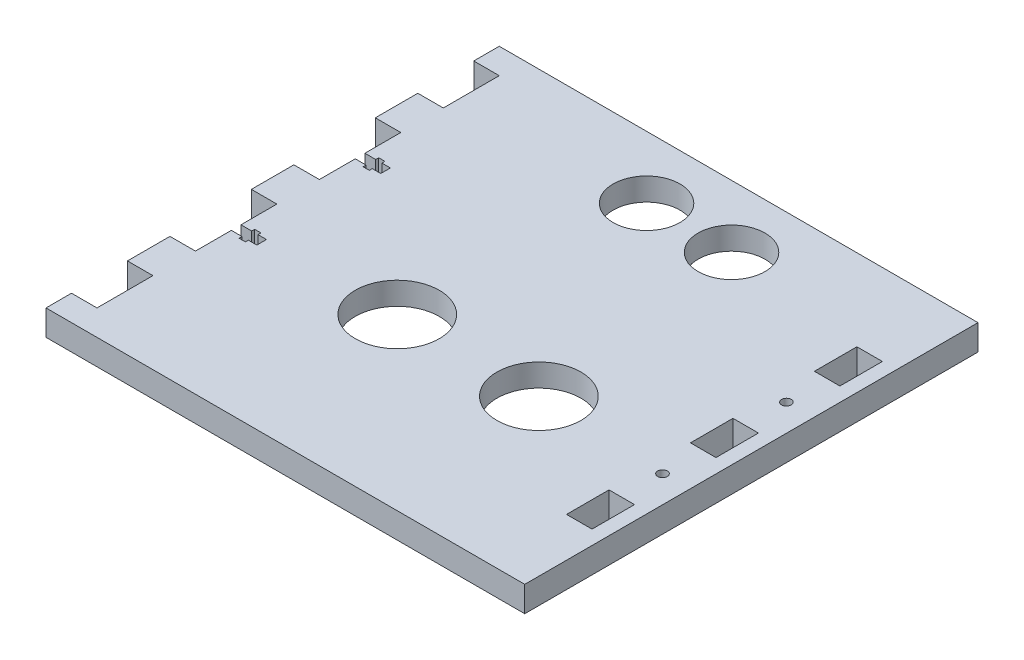
SolidWorks part; units mm, degrees
ref_plane "Front Plane" through (0, 0, 0) normal (0, 0, 1) x (1, 0, 0)
ref_plane "Top Plane" through (0, 0, 0) normal (0, 1, 0) x (1, 0, 0)
ref_plane "Right Plane" through (0, 0, 0) normal (1, 0, 0) x (0, 0, -1)
sketch "Sketch1" plane through (0, 0, 0) normal (0, 1, 0) x (1, 0, 0)
  line L1 (80, -80) -> (-80, -80)
  line L2 (80, -80) -> (80, 80)
  line L3 (80, 80) -> (-80, 80)
  line L4 (-80, -80) -> (-80, 80)
  line L5 (80, -80) -> (-80, 80) construction
  line L6 (80, 80) -> (-80, -80) construction
  point P0 (0, 0)
  dimension "D1" = 160
extrude "Boss-Extrude1" add sketch "Sketch1" along normal blind 9
sketch "Sketch2" plane through (0, 9, 0) normal (0, 1, 0) x (1, 0, 0)
  line L0 (-80, 80) -> (-80, -80) construction
  line L1 (-80, -7.5) -> (-89, -7.5)
  line L2 (-80, -7.5) -> (-80, 7.5)
  line L3 (-80, 7.5) -> (-89, 7.5)
  line L4 (-89, -7.5) -> (-89, 7.5)
  line L5 (-80, 0) -> (0, 0) construction
  line L6 (-80, 80) -> (-80, 51.25) construction
  line L7 (-80, 51.25) -> (-89, 51.25)
  line L8 (-80, 51.25) -> (-80, 36.25)
  line L9 (-80, 36.25) -> (-89, 36.25)
  line L10 (-89, 51.25) -> (-89, 36.25)
  line L11 (-80, -36.25) -> (-89, -36.25)
  line L12 (-80, -36.25) -> (-80, -51.25)
  line L13 (-80, -51.25) -> (-89, -51.25)
  line L14 (-89, -36.25) -> (-89, -51.25)
  line L15 (-80, 36.25) -> (-80, 7.5) construction
  line L16 (-80, -7.5) -> (-80, -36.25) construction
  line L17 (-80, -51.25) -> (-80, -80) construction
  line L19 (-80, 80) -> (-89, 80)
  line L20 (-80, 80) -> (-80, 71)
  line L21 (-80, 71) -> (-89, 71)
  line L22 (-89, 80) -> (-89, 71)
  line L23 (-80, -80) -> (-89, -80)
  line L24 (-80, -80) -> (-80, -71)
  line L25 (-80, -71) -> (-89, -71)
  line L26 (-89, -80) -> (-89, -71)
  dimension "D1" = 9
  dimension "D2" = 15
  dimension "D3" = 9
extrude "Boss-Extrude2" add sketch "Sketch2" against normal up to surface (9 mm away) up to face at (0, 0, 0)
sketch "Sketch3" plane through (0, 9, 0) normal (0, 1, 0) x (1, 0, 0)
  line L1 (75, 51.25) -> (66, 51.25)
  line L2 (75, 51.25) -> (75, 36.25)
  line L3 (75, 36.25) -> (66, 36.25)
  line L4 (66, 51.25) -> (66, 36.25)
  line L5 (-80, 51.25) -> (-89, 51.25) construction
  line L6 (75, 7.5) -> (66, 7.5)
  line L7 (75, 7.5) -> (75, -7.5)
  line L8 (75, -7.5) -> (66, -7.5)
  line L9 (66, 7.5) -> (66, -7.5)
  line L10 (75, -36.25) -> (66, -36.25)
  line L11 (75, -36.25) -> (75, -51.25)
  line L12 (75, -51.25) -> (66, -51.25)
  line L13 (66, -36.25) -> (66, -51.25)
  line L14 (-80, 7.5) -> (-89, 7.5) construction
  line L15 (-89, -7.5) -> (-80, -7.5) construction
  line L16 (-89, -51.25) -> (-80, -51.25) construction
  line L17 (80, -80) -> (80, 80) construction
  line L18 (70.5, 36.25) -> (70.5, 7.5) construction
  line L19 (70.5, 7.5) -> (70.5, -7.5) construction
  line L20 (70.5, -7.5) -> (70.5, -36.25) construction
  line L21 (70.5, -36.25) -> (70.5, -51.25) construction
  line L22 (70.5, -51.25) -> (70.5, -80) construction
  line L23 (-89, -80) -> (80, -80) construction
  line L24 (70.5, 51.25) -> (70.5, 80) construction
  line L25 (80, 80) -> (-89, 80) construction
  circle A0 centre (70.5, 21.875) radius 1.7
  circle A1 centre (70.5, -21.875) radius 1.7
  dimension "D2" = 3.4
  dimension "D1" = 5
extrude "Cut-Extrude1" cut sketch "Sketch3" against normal through all
sketch "Sketch4" plane through (0, 9, 0) normal (0, 1, 0) x (1, 0, 0)
  line L1 (-80, 36.25) -> (-80, 7.5) construction
  line L2 (-89, 51.25) -> (-89, 36.25) construction
  line L3 (-89, 0) -> (0, 0) construction
  line L4 (-89, 7.5) -> (-89, -7.5) construction
  line L5 (-80, -21.875) -> (-71, -21.875) construction
  line L6 (-80, 23.575) -> (-76.2, 23.575)
  line L7 (-80, -23.575) -> (-80, -20.175)
  line L8 (-76.2, -20.175) -> (-80, -20.175)
  line L9 (-76.2, -19.125) -> (-76.2, -20.175)
  line L10 (-74, -19.125) -> (-76.2, -19.125)
  line L11 (-74, -20.175) -> (-74, -19.125)
  line L12 (-71, -20.175) -> (-74, -20.175)
  line L13 (-71, -23.575) -> (-71, -20.175)
  line L14 (-74, -23.575) -> (-71, -23.575)
  line L15 (-74, -24.625) -> (-74, -23.575)
  line L16 (-76.2, -24.625) -> (-74, -24.625)
  line L17 (-76.2, -23.575) -> (-76.2, -24.625)
  line L18 (-80, -23.575) -> (-76.2, -23.575)
  line L20 (-76.2, 23.575) -> (-76.2, 24.625)
  line L21 (-76.2, 24.625) -> (-74, 24.625)
  line L22 (-74, 24.625) -> (-74, 23.575)
  line L23 (-74, 23.575) -> (-71, 23.575)
  line L24 (-71, 23.575) -> (-71, 20.175)
  line L25 (-71, 20.175) -> (-74, 20.175)
  line L26 (-74, 20.175) -> (-74, 19.125)
  line L27 (-74, 19.125) -> (-76.2, 19.125)
  line L28 (-76.2, 19.125) -> (-76.2, 20.175)
  line L29 (-76.2, 20.175) -> (-80, 20.175)
  line L30 (-80, 23.575) -> (-80, 20.175)
  line L31 (-80, 21.875) -> (-71, 21.875) construction
  dimension "D1" = 3.4
  dimension "D2" = 18
  dimension "D3" = 2.2
  dimension "D4" = 5.5
  dimension "D5" = 3
extrude "Cut-Extrude2" cut sketch "Sketch4" against normal through all
sketch "Sketch5" plane through (0, 0, 0) normal (0, -1, 0) x (1, 0, 0)
  line L0 (25, 20) -> (-25, 20) construction
  line L1 (25, 20) -> (80, 20) construction
  line L2 (80, 80) -> (80, -80) construction
  line L3 (80, -58) -> (15, -58) construction
  line L4 (15, -58) -> (-15, -58) construction
  line L5 (80, -80) -> (-89, -80) construction
  line L6 (0, 0) -> (0, 20) construction
  line L7 (-89, 80) -> (80, 80) construction
  line L8 (0, -58) -> (0, 0) construction
  circle A0 centre (25, 20) radius 14.825
  circle A2 centre (-25, 20) radius 14.825
  circle A4 centre (15, -58) radius 11.8
  circle A5 centre (-15, -58) radius 11.8
  dimension "D1" = 50
  dimension "D5" = 29.65
  dimension "D9" = 23.6
  dimension "D2" = 60
  dimension "D6" = 22
  dimension "D8" = 30
extrude "Cut-Extrude3" cut sketch "Sketch5" against normal through all
sketch "Sketch6" plane through (0, 0, 0) normal (0, -1, 0) x (1, 0, 0)
  line L0 (15, -58) -> (-15, -58) construction
  line L1 (5, 40) -> (45, 40)
  line L2 (5, 40) -> (5, 0)
  line L3 (5, 0) -> (45, 0)
  line L4 (45, 40) -> (45, 0)
  line L5 (5, 40) -> (45, 0) construction
  line L6 (5, 0) -> (45, 40) construction
  line L7 (-5, 40) -> (-45, 40)
  line L8 (-5, 40) -> (-5, 0)
  line L9 (-5, 0) -> (-45, 0)
  line L10 (-45, 40) -> (-45, 0)
  line L11 (-5, 40) -> (-45, 0) construction
  line L12 (-5, 0) -> (-45, 40) construction
  line L13 (31, -44) -> (-31, -44)
  line L14 (31, -44) -> (31, -72)
  line L15 (31, -72) -> (-31, -72)
  line L16 (-31, -44) -> (-31, -72)
  line L17 (31, -44) -> (-31, -72) construction
  line L18 (31, -72) -> (-31, -44) construction
  circle A0 centre (25, 20) radius 14.825 construction
  circle A1 centre (-25, 20) radius 14.825 construction
  circle A2 centre (25, 20) radius 14.825 construction
  circle A3 centre (-25, 20) radius 14.825 construction
  circle A4 centre (-15, -58) radius 11.8 construction
  circle A5 centre (15, -58) radius 11.8 construction
  circle A6 centre (-15, -58) radius 11.8 construction
  circle A7 centre (15, -58) radius 11.8 construction
  point P14 (0, -58)
  point P25 (0, -58)
  dimension "D1" = 20
  dimension "D2" = 14
  dimension "D3" = 16
extrude "Cut-Extrude4" cut sketch "Sketch6" against normal blind 1
fillet "Fillet1" radius 8 8 edges at (-45, 0.5, 0) (-5, 0.5, 0) (-5, 0.5, 40) (-45, 0.5, 40) (5, 0.5, 40) (45, 0.5, 40) (45, 0.5, 0) (5, 0.5, 0)
fillet "Fillet2" radius 4 4 edges at (31, 0.5, -44) (31, 0.5, -72) (-31, 0.5, -44) (-31, 0.5, -72)
sketch "Sketch7" plane through (0, 0, 0) normal (0, -1, 0) x (1, 0, 0)
  line L0 (5, 32) -> (5, 50) construction
  line L1 (5, 50) -> (55, 50) construction
  line L2 (-45, 32) -> (-45, 50) construction
  line L3 (-45, 50) -> (5, 50) construction
  line L4 (-45, 32) -> (-45, 8) construction
  line L5 (15, -58) -> (-15, -58) construction
  line L6 (0, -58) -> (0, -33) construction
  line L7 (0, -33) -> (-31, -33) construction
  line L8 (0, -33) -> (31, -33) construction
  line L9 (31, -33) -> (31, -58) construction
  line L10 (31, -68) -> (31, -48) construction
  arc A0 (-37, 40) -> (-45, 32) centre (-37, 32) ccw construction
  text T0 "B" font "Nes Controller" height 8
  text T1 "A" font "Nes Controller" height 8
  text T2 "select" font "Nes Controller" height 4
  text T3 "start" font "Nes Controller" height 4
  dimension "D1" = 18
  dimension "D2" = 25
extrude "Cut-Extrude5" cut sketch "Sketch7" against normal blind 1
